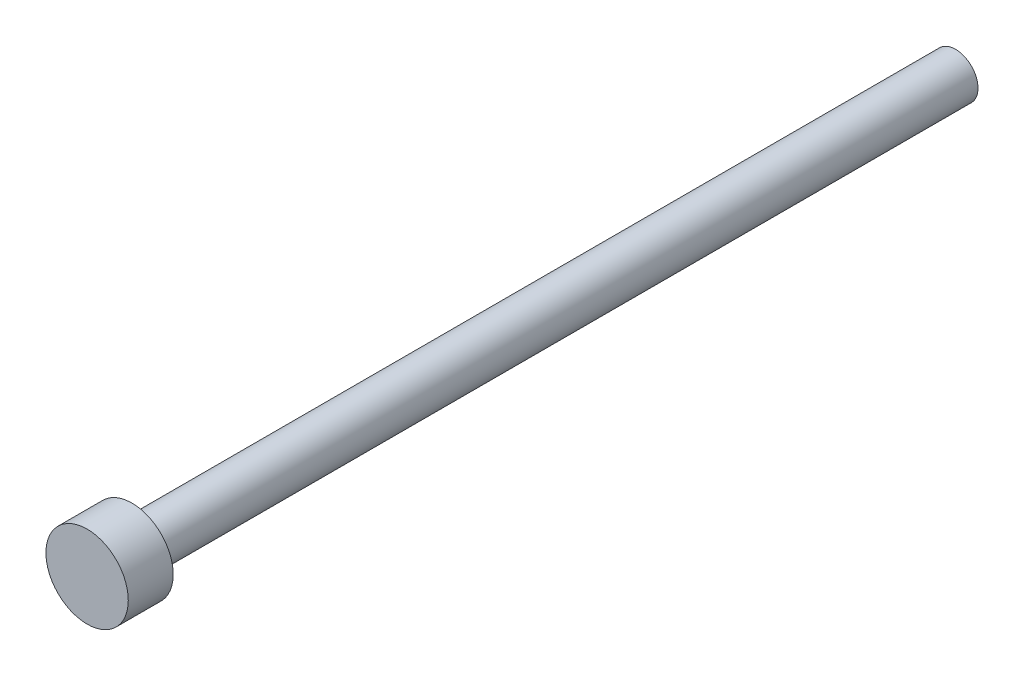
SolidWorks part; units mm, degrees
ref_plane "Front Plane" through (0, 0, 0) normal (0, 0, 1) x (1, 0, 0)
ref_plane "Top Plane" through (0, 0, 0) normal (0, 1, 0) x (1, 0, 0)
ref_plane "Right Plane" through (0, 0, 0) normal (1, 0, 0) x (0, 0, -1)
sketch "Sketch1" plane through (0, 0, 0) normal (0, 0, 1) x (1, 0, 0)
  circle A0 centre (0, 0) radius 1.5
extrude "Thread_Envelope" add sketch "Sketch1" along normal blind 55 from offset 55
sketch "Sketch2" plane through (0, 0, 0) normal (0, 0, 1) x (1, 0, 0)
  circle A0 centre (0, 0) radius 2.75
extrude "Head_Envelope" add sketch "Sketch2" along normal blind 3
